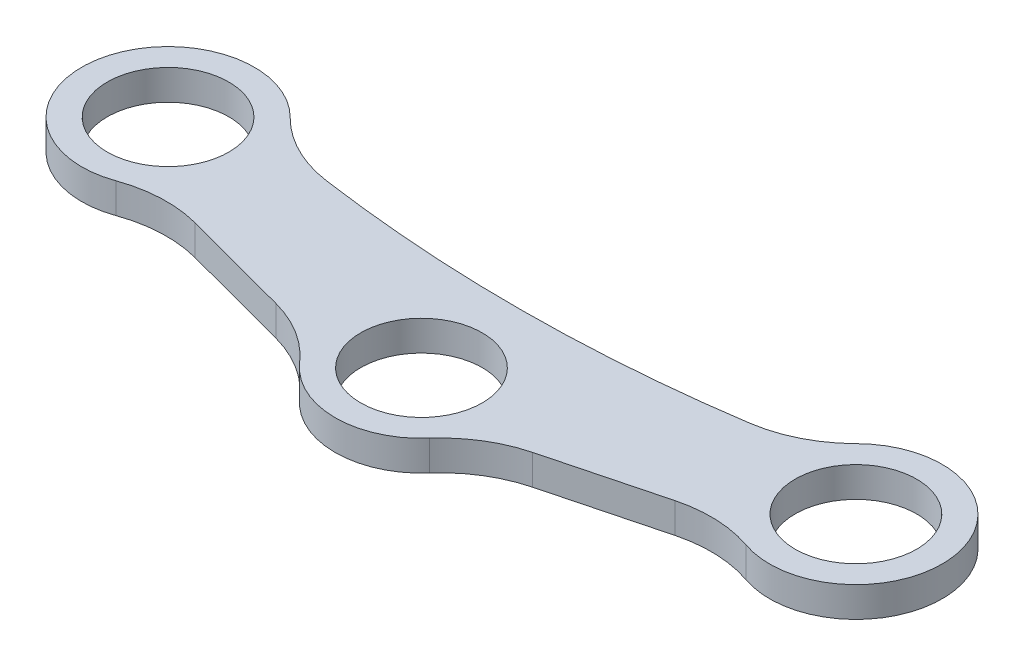
SolidWorks part; units mm, degrees
material "ABS"
ref_plane "Front Plane" through (0, 0, 0) normal (0, 0, 1) x (1, 0, 0)
ref_plane "Top Plane" through (0, 0, 0) normal (0, 1, 0) x (1, 0, 0)
ref_plane "Right Plane" through (0, 0, 0) normal (1, 0, 0) x (0, 0, -1)
sketch "Sketch1" plane through (0, 0, 0) normal (0, 1, 0) x (1, 0, 0)
  line L0 (-114, 30) -> (0, 30) construction
  line L1 (0, 30) -> (114, 30) construction
  line L2 (-115.9454, 22.7049) -> (-2.0449, -7.6685)
  line L3 (116.0759, 22.029) -> (2.0002, -7.6803)
  line L4 (-114, 30) -> (0, 0) construction
  line L5 (0, 0) -> (114, 30) construction
  line L6 (-98.5213, 25.9267) -> (-20.1078, 5.2915) construction
  line L7 (-97.5271, 29.7047) -> (-19.1136, 9.0696)
  line L8 (-99.5156, 22.1486) -> (-21.102, 1.5135)
  line L9 (20.1078, 5.2915) -> (98.5213, 25.9267) construction
  line L10 (19.1136, 9.0696) -> (97.5271, 29.7047)
  line L11 (21.102, 1.5135) -> (99.5156, 22.1486)
  circle A0 centre (0, 0) radius 4.05
  circle A1 centre (114, 30) radius 4.05
  circle A2 centre (-114, 30) radius 4.05
  arc A3 (-112.2929, 37.3545) -> (-115.9454, 22.7049) centre (-114, 30) ccw
  arc A4 (-2.0449, -7.6685) -> (2.0002, -7.6803) centre (0, 0) ccw
  arc A5 (105.7631, 30) -> (106.0343, 27.9038) centre (114, 30) ccw
  arc A6 (-112.2929, 37.3545) -> (112.0905, 38.0125) centre (-1.5, 514.6646) ccw
  arc A7 (-97.5271, 29.7047) -> (-99.5156, 22.1486) centre (-98.5213, 25.9267) ccw
  arc A8 (-21.102, 1.5135) -> (-19.1136, 9.0696) centre (-20.1078, 5.2915) ccw
  arc A9 (19.1136, 9.0696) -> (21.102, 1.5135) centre (20.1078, 5.2915) ccw
  arc A10 (99.5156, 22.1486) -> (97.5271, 29.7047) centre (98.5213, 25.9267) ccw
  arc A11 (-106.6986, 28.0786) -> (-106.45, 30) centre (-114, 30) ccw
  arc A12 (116.0759, 22.029) -> (112.0905, 38.0125) centre (114, 30) ccw
  point P20 (-59.3146, 15.6091)
  point P27 (59.3146, 15.6091)
  dimension "D1" = 8.1
  dimension "D2" = 114
  dimension "D3" = 30
  dimension "D4" = 114
  dimension "D5" = 15.1
  dimension "D6" = 490
extrude "Boss-Extrude1" add sketch "Sketch1" along normal mid plane 10
scale "Scale1" bodies to scale 104 scale about centroid uniform scaling yes scale factor 0.471698
sketch "Sketch2" plane through (0, 2.3585, 0) normal (0, 1, 0) x (1, 0, 0)
  line L4 (2.7857, 1.5154) -> (56.595, 15.5292)
  line L5 (-54.8878, 15.854) -> (-1.1612, 1.5269)
  line L6 (13.487, 4.3024) -> (45.991, 12.7676)
  line L7 (-44.0816, 12.9724) -> (-11.8461, 4.3762)
  circle A4 centre (54.6077, 23.16) radius 1.9104 construction
  circle A5 centre (0.8341, 9.0091) radius 1.9104 construction
  circle A6 centre (-52.9395, 23.16) radius 1.9104 construction
  circle A7 centre (54.6077, 23.16) radius 1.9104
  arc A8 (56.595, 15.5292) -> (52.7797, 30.8306) centre (54.6077, 23.16) ccw
  arc A9 (-51.2298, 30.5255) -> (52.7797, 30.8306) centre (0.1265, 251.7754) ccw
  arc A10 (-51.2298, 30.5255) -> (-54.8878, 15.854) centre (-52.9395, 23.16) ccw
  arc A11 (-1.1612, 1.5269) -> (2.7857, 1.5154) centre (0.8341, 9.0091) ccw
  arc A13 (-40.4555, 28.2982) -> (42.2446, 28.5825) centre (0.1265, 251.7754) ccw
  circle A16 centre (0.8341, 9.0091) radius 1.9104
  circle A17 centre (-52.9395, 23.16) radius 1.9104
  arc A18 (-40.4555, 28.2982) -> (-44.0816, 12.9724) centre (-52.9395, 23.16) ccw
  arc A19 (-11.8461, 4.3762) -> (13.487, 4.3024) centre (0.8341, 9.0091) ccw
  arc A20 (45.991, 12.7676) -> (42.2446, 28.5825) centre (54.6077, 23.16) ccw
  dimension "D2" = 27
  dimension "D1" = 4
extrude "Boss-Extrude2" add sketch "Sketch2" against normal through all
sketch "Sketch3" plane through (0, 2.3585, 0) normal (0, 1, 0) x (1, 0, 0)
  circle A0 centre (-52.9395, 23.16) radius 9.5
  circle A1 centre (0.8341, 9.0091) radius 9.5
  circle A2 centre (54.6077, 23.16) radius 9.5
  dimension "D1" = 19
extrude "Cut-Extrude1" cut sketch "Sketch3" against normal through all
fillet "Fillet1" radius 20 6 edges at (-44.0816, 0, -12.9724) (-11.8461, 0, -4.3762) (13.487, 0, -4.3024) (45.991, 0, -12.7676) (42.2446, 0, -28.5825) (-40.4555, 0, -28.2982)
